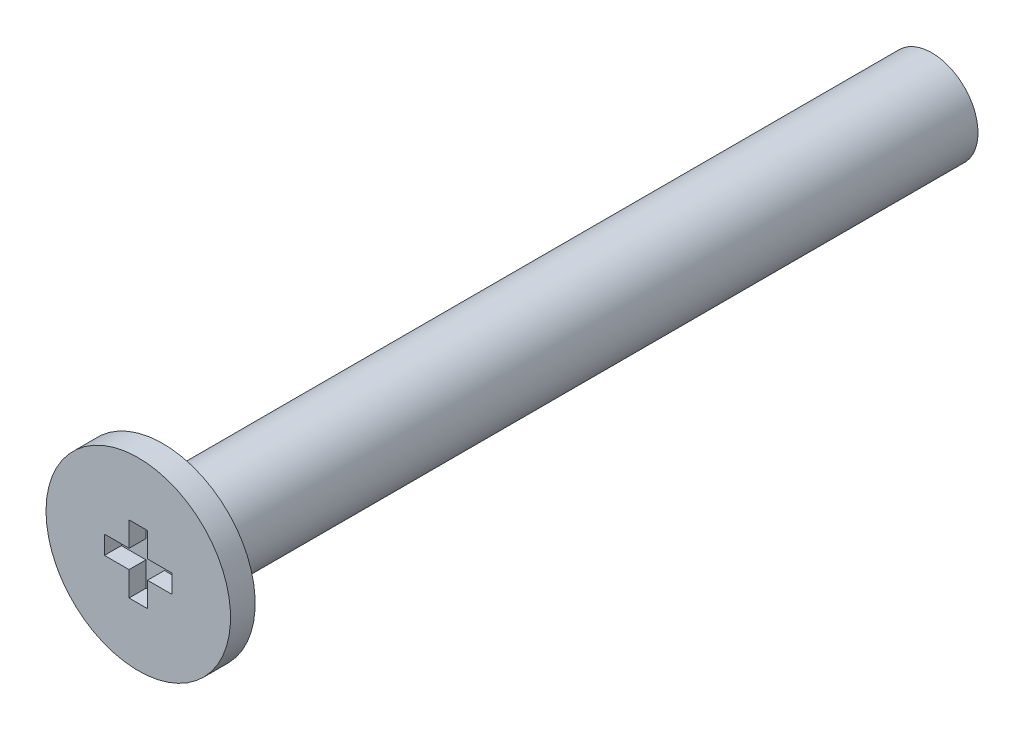
SolidWorks part; units mm, degrees
ref_plane "前视基准面" through (0, 0, 0) normal (0, 0, 1) x (1, 0, 0)
ref_plane "上视基准面" through (0, 0, 0) normal (0, 1, 0) x (1, 0, 0)
ref_plane "右视基准面" through (0, 0, 0) normal (1, 0, 0) x (0, 0, -1)
other "Configuration Table"
sketch "草图1" plane through (0, 0, 0) normal (0, 0, 1) x (1, 0, 0)
  circle A0 centre (0, 0) radius 1.5
extrude "标准杆径_头下长度" add sketch "草图1" against normal blind 25
sketch "草图2" plane through (0, 0, 0) normal (0, 0, 1) x (1, 0, 0)
  circle A0 centre (0, 0) radius 2.75
sketch "草图4" plane through (0, 0, 0) normal (0, 1, 0) x (1, 0, 0)
  line L0 (0, 0) -> (3.45, 0)
  line L1 (3.45, 0) -> (3.45, -0.3426)
  line L2 (0, -1.9) -> (0, 0)
  line L3 (0, 2) -> (0, -3.9) construction
  arc A0 (3.45, -0.3426) -> (0, -1.9) centre (0, 2.7) cw
sketch "草图5" plane through (0, 0, 0) normal (0, 0, 1) x (1, 0, 0)
  line L0 (-0.3, -1.45) -> (0.3, -1.45)
  line L1 (0.3, -1.45) -> (0.3, -0.3)
  line L2 (0.3, -0.3) -> (1.45, -0.3)
  line L3 (1.45, -0.3) -> (1.45, 0.3)
  line L4 (1.45, 0.3) -> (0.3, 0.3)
  line L5 (0.3, 0.3) -> (0.3, 1.45)
  line L6 (0.3, 1.45) -> (-0.3, 1.45)
  line L7 (-0.3, 1.45) -> (-0.3, 0.3)
  line L8 (-0.3, 0.3) -> (-1.45, 0.3)
  line L9 (-1.45, 0.3) -> (-1.45, -0.3)
  line L10 (-1.45, -0.3) -> (-0.3, -0.3)
  line L11 (-0.3, -0.3) -> (-0.3, -1.45)
sketch "草图6" plane through (0, 0, 0) normal (0, 1, 0) x (1, 0, 0)
  line L0 (0, 0) -> (3, 0)
  line L1 (3, 0) -> (3, -0.8)
  line L2 (3, -0.8) -> (0, -0.8)
  line L3 (0, -0.8) -> (0, 0)
  line L4 (0, 2) -> (0, -2.8) construction
revolve "已确认_十字槽超薄头" add sketch "草图6" angle 360 about L4
sketch "草图7" plane through (0, 0, 0) normal (0, 0, 1) x (1, 0, 0)
  line L0 (-0.3, -1.1) -> (0.3, -1.1)
  line L1 (0.3, -1.1) -> (0.3, -0.3)
  line L2 (0.3, -0.3) -> (1.1, -0.3)
  line L3 (1.1, -0.3) -> (1.1, 0.3)
  line L4 (1.1, 0.3) -> (0.3, 0.3)
  line L5 (0.3, 0.3) -> (0.3, 1.1)
  line L6 (0.3, 1.1) -> (-0.3, 1.1)
  line L7 (-0.3, 1.1) -> (-0.3, 0.3)
  line L8 (-0.3, 0.3) -> (-1.1, 0.3)
  line L9 (-1.1, 0.3) -> (-1.1, -0.3)
  line L10 (-1.1, -0.3) -> (-0.3, -0.3)
  line L11 (-0.3, -0.3) -> (-0.3, -1.1)
extrude "十字槽_PH1_简化" cut sketch "草图7" against normal blind 0.56 from offset 0.81
